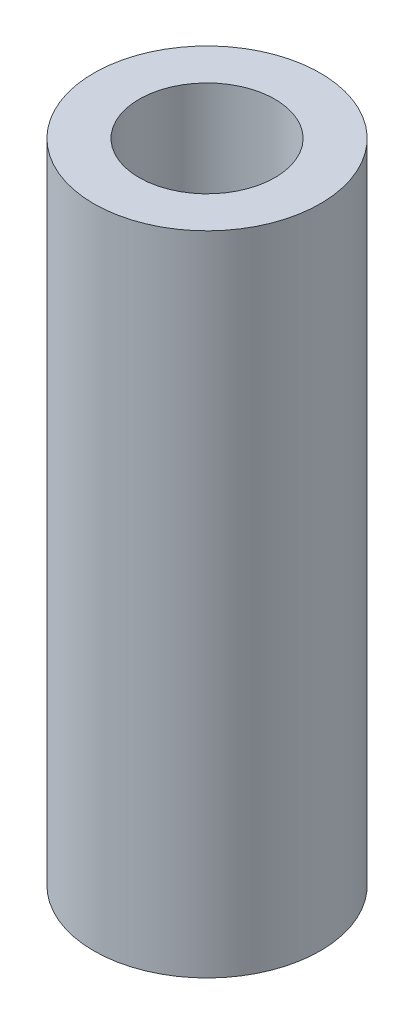
SolidWorks part; units mm, degrees
material "ABS"
ref_plane "前视基准面" through (0, 0, 0) normal (0, 0, 1) x (1, 0, 0)
ref_plane "上视基准面" through (0, 0, 0) normal (0, 1, 0) x (1, 0, 0)
ref_plane "右视基准面" through (0, 0, 0) normal (1, 0, 0) x (0, 0, -1)
sketch "草图1" plane through (0, 0, 0) normal (0, 1, 0) x (1, 0, 0)
  circle A0 centre (0, 0) radius 2.1
  circle A1 centre (0, 0) radius 3.5
  dimension "D1" = 7
  dimension "D2" = 4.2
extrude "凸台-拉伸1" add sketch "草图1" along normal blind 20
